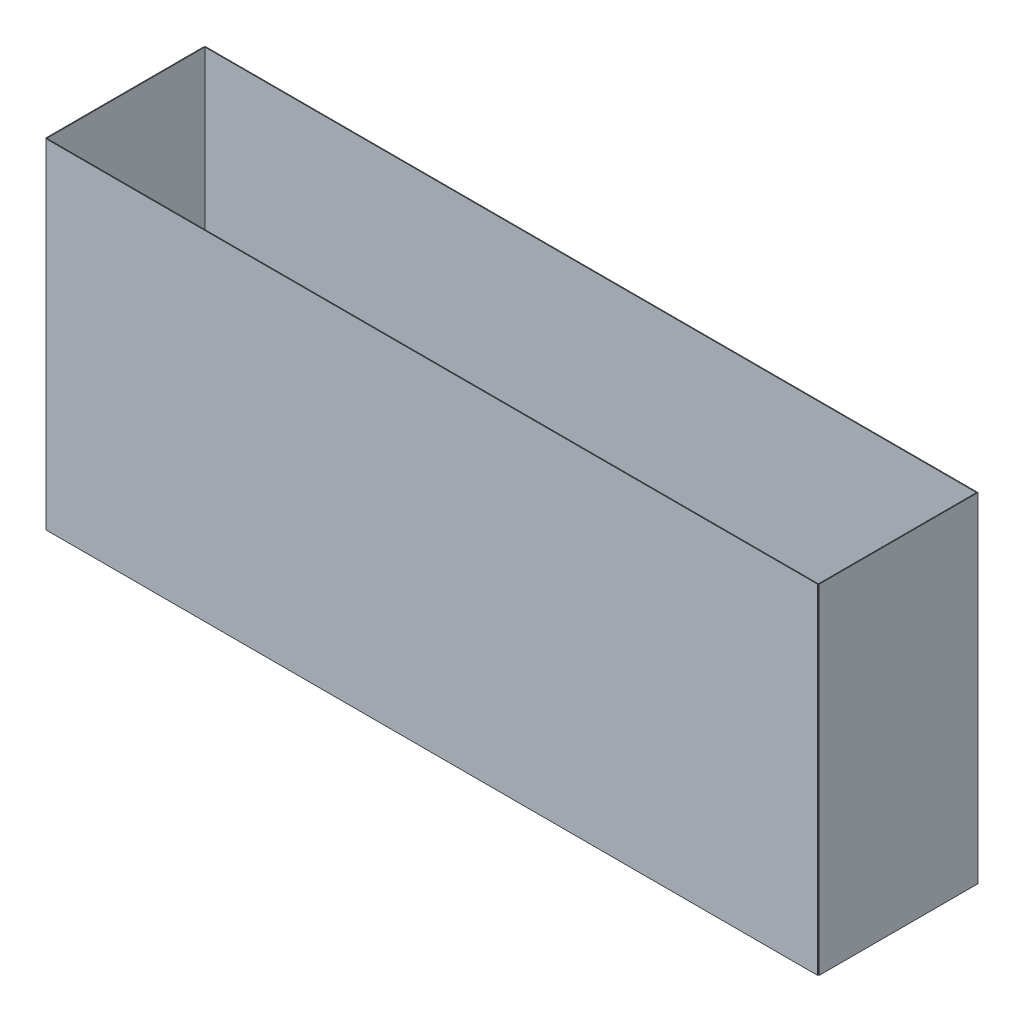
SolidWorks part; units mm, degrees
ref_plane "Front Plane" through (0, 0, 0) normal (0, 0, 1) x (1, 0, 0)
ref_plane "Top Plane" through (0, 0, 0) normal (0, 1, 0) x (1, 0, 0)
ref_plane "Right Plane" through (0, 0, 0) normal (1, 0, 0) x (0, 0, -1)
other "Gráfico1"
other "Gráfico (Cerrada) -1"
other "Gráfico (Cerrada) -2"
other "Gráfico (Cerrada) -3"
sketch "Croquis1" plane through (0, 0, -10) normal (0, 0, -1) x (-1, 0, 0)
  line L0 (0, 11.66) -> (0, -11.66) construction
  line L1 (53.004, -27.0651) -> (-49.496, -27.0651)
  line L2 (53.004, -27.0651) -> (53.004, 17.9349)
  line L3 (53.004, 17.9349) -> (-49.496, 17.9349)
  line L4 (-49.496, -27.0651) -> (-49.496, 17.9349)
  line L5 (53.004, 52.9349) -> (53.004, -62.0651) construction
  line L7 (-49.496, -62.0651) -> (-49.496, 52.9349) construction
  line L9 (-49.496, 17.9349) -> (-49.496, 52.9349) construction
  line L10 (-49.496, -27.0651) -> (-49.496, -62.0651) construction
  point P0 (0, -4.1376)
  dimension "D1" = 45
extrude "Saliente-Extruir1" add sketch "Croquis1" along normal blind 0.1
sketch "Croquis2" plane through (49.496, 0, 0) normal (1, 0, 0) x (0, 0, -1)
  line L0 (-11, 52.9349) -> (-11, -62.0651) construction
  line L1 (10.1, -27.0651) -> (-11, -27.0651)
  line L2 (10.1, -27.0651) -> (10.1, 17.9349)
  line L3 (10.1, 17.9349) -> (-11, 17.9349)
  line L4 (-11, -27.0651) -> (-11, 17.9349)
  dimension "D1" = 45
extrude "Saliente-Extruir2" add sketch "Croquis2" along normal blind 0.1
sketch "Croquis3" plane through (0, 0, 11) normal (0, 0, 1) x (1, 0, 0)
  line L0 (-53.004, 52.9349) -> (-53.004, -62.0651) construction
  line L1 (49.496, 17.9349) -> (-53.004, 17.9349)
  line L2 (49.496, 17.9349) -> (49.496, -27.0651)
  line L3 (49.496, -27.0651) -> (-53.004, -27.0651)
  line L4 (-53.004, 17.9349) -> (-53.004, -27.0651)
  dimension "D1" = 45
extrude "Saliente-Extruir3" add sketch "Croquis3" along normal blind 0.1
sketch "Croquis4" plane through (-53.004, 0, 0) normal (-1, 0, 0) x (0, 0, 1)
  line L1 (11, 17.9349) -> (-10, 17.9349)
  line L2 (11, 17.9349) -> (11, -27.0651)
  line L3 (11, -27.0651) -> (-10, -27.0651)
  line L4 (-10, 17.9349) -> (-10, -27.0651)
extrude "Saliente-Extruir4" add sketch "Croquis4" along normal blind 0.1
